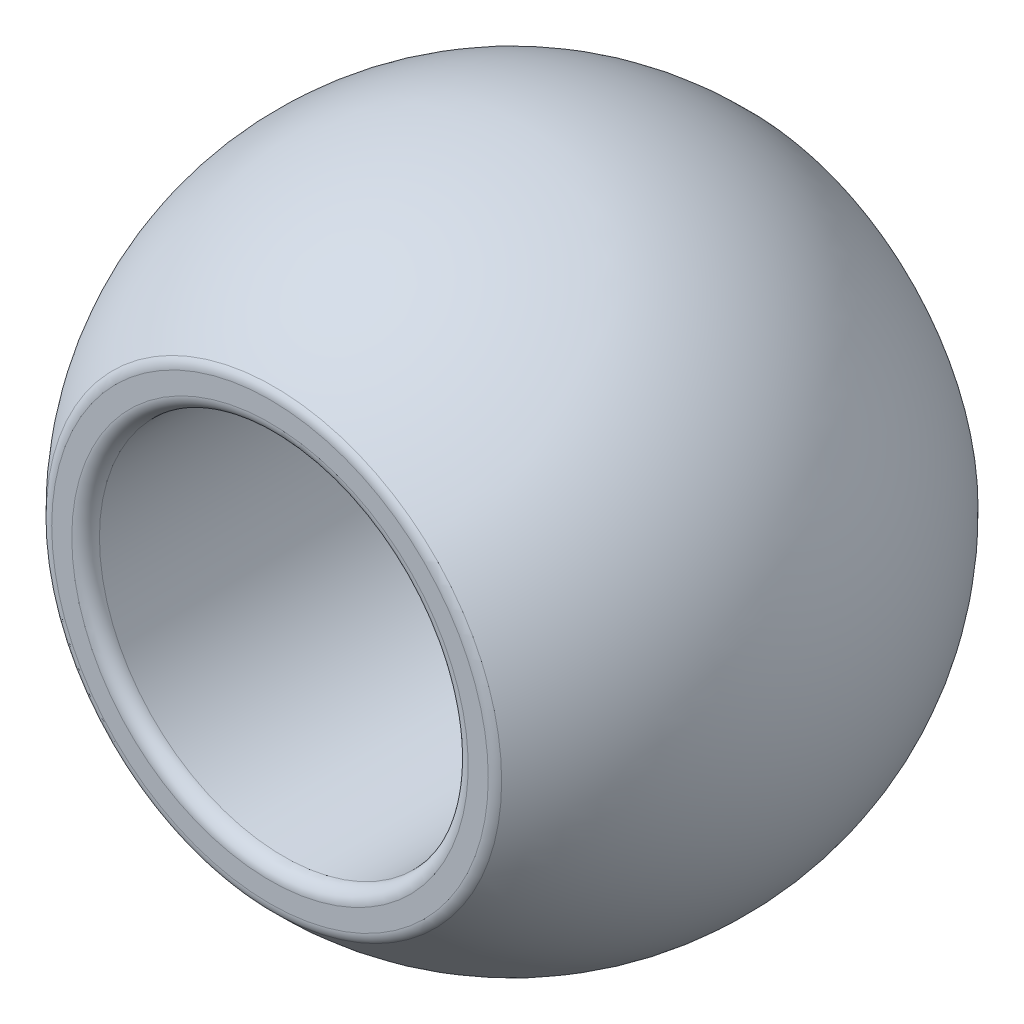
SolidWorks part; units mm, degrees
material "AISI 1020"
ref_plane "Plano frontal" through (0, 0, 0) normal (0, 0, 1) x (1, 0, 0)
ref_plane "Plano superior" through (0, 0, 0) normal (0, 1, 0) x (1, 0, 0)
ref_plane "Plano direito" through (0, 0, 0) normal (1, 0, 0) x (0, 0, -1)
sketch "Esboço1" plane through (0, 0, 0) normal (0, 0, 1) x (1, 0, 0)
  line L0 (0, -14.3) -> (0, 14.3)
  arc A0 (0, -14.3) -> (0, 14.3) centre (0, 0) ccw
  dimension "D1" = 28.6
revolve "Revolução1" add sketch "Esboço1" angle 360 about L0
sketch "Esboço2" plane through (0, 0, 0) normal (1, 0, 0) x (0, 0, -1)
  line L1 (-10.5, 15) -> (-25.5, 15)
  line L2 (-10.5, 15) -> (-10.5, -15)
  line L3 (-10.5, -15) -> (-25.5, -15)
  line L4 (-25.5, 15) -> (-25.5, -15)
  line L5 (10.5, 15) -> (25.5, 15)
  line L6 (10.5, 15) -> (10.5, -15)
  line L7 (10.5, -15) -> (25.5, -15)
  line L8 (25.5, 15) -> (25.5, -15)
  point P9 (10.5, 0)
  dimension "D1" = 15
  dimension "D2" = 30
  dimension "D3" = 21
  dimension "D4" = 10.5
extrude "Corte-extrusão1" cut sketch "Esboço2" against normal through all both and the other way through all
sketch "Esboço3" plane through (0, 0, 10.5) normal (0, 0, 1) x (1, 0, 0)
  circle A0 centre (0, 0) radius 8
  dimension "D1" = 16
extrude "Corte-extrusão2" cut sketch "Esboço3" against normal through all
fillet "Filete1" radius 0.6 4 edges at (8, 0, -10.5) (8, 0, 10.5) (9.7077, 0, -10.5) (-9.7077, 0, 10.5)
scale "Scale1" scale about centroid uniform scaling yes scale factor 0.5
sketch "Sketch1" plane through (0, 0, 0) normal (0, 1, 0) x (1, 0, 0)
  point P0 (0, 0)
